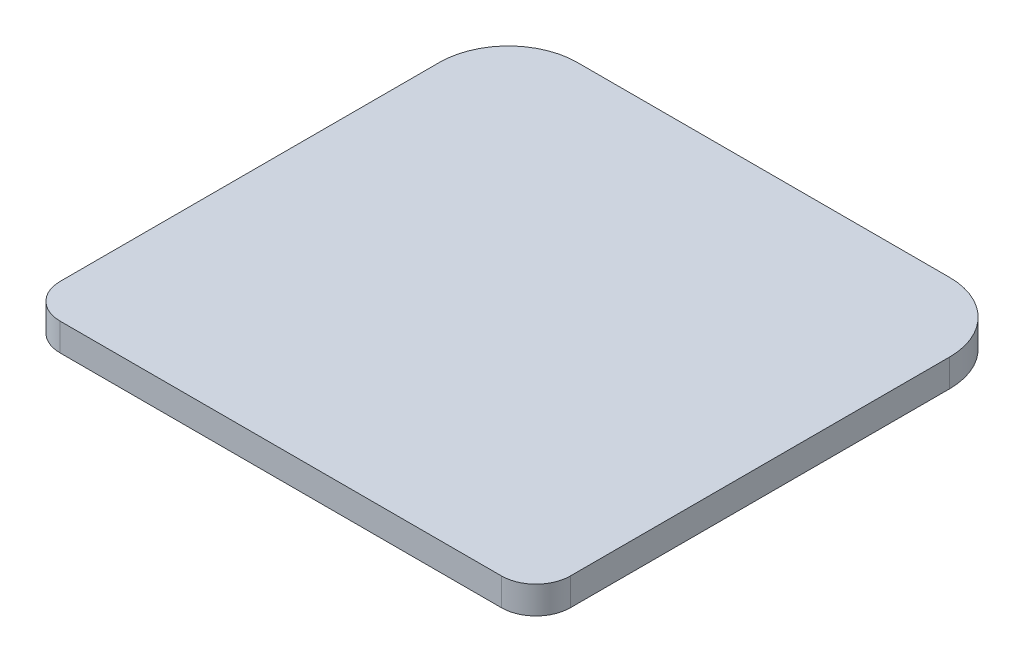
SolidWorks part; units mm, degrees
ref_plane "Front Plane" through (0, 0, 0) normal (0, 0, 1) x (1, 0, 0)
ref_plane "Top Plane" through (0, 0, 0) normal (0, 1, 0) x (1, 0, 0)
ref_plane "Right Plane" through (0, 0, 0) normal (1, 0, 0) x (0, 0, -1)
sketch "Sketch1" plane through (0, 0, 0) normal (0, 1, 0) x (1, 0, 0)
  line L1 (-7.4, -7) -> (7.4, -7)
  line L2 (-7.4, -7) -> (-7.4, 7)
  line L3 (-7.4, 7) -> (7.4, 7)
  line L4 (7.4, -7) -> (7.4, 7)
  line L5 (-7.4, -7) -> (7.4, 7) construction
  line L6 (-7.4, 7) -> (7.4, -7) construction
  point P0 (0, 0)
  dimension "D1" = 14.8
  dimension "D2" = 14
extrude "Boss-Extrude1" add sketch "Sketch1" along normal blind 0.8
fillet "Fillet1" radius 2 2 edges at (-7.4, 0.4, -7) (7.4, 0.4, -7)
fillet "Fillet2" radius 1 2 edges at (-7.4, 0.4, 7) (7.4, 0.4, 7)
